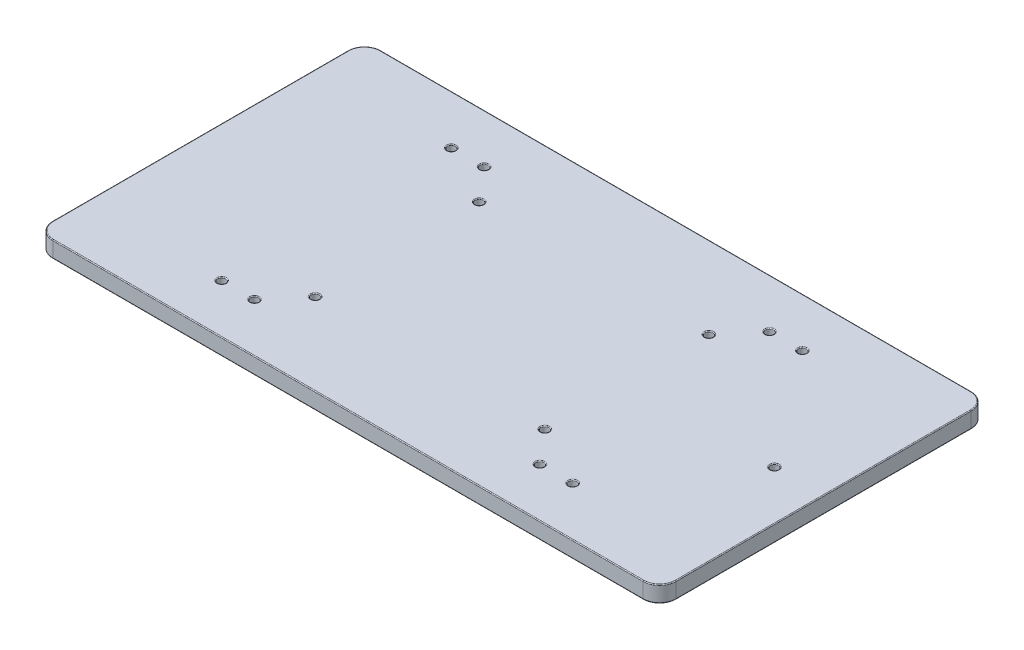
SolidWorks part; units mm, degrees
ref_plane "Front Plane" through (0, 0, 0) normal (0, 0, 1) x (1, 0, 0)
ref_plane "Top Plane" through (0, 0, 0) normal (0, 1, 0) x (1, 0, 0)
ref_plane "Right Plane" through (0, 0, 0) normal (1, 0, 0) x (0, 0, -1)
sketch "Sketch1" plane through (0, 0, 0) normal (0, 1, 0) x (1, 0, 0)
  line L0 (80, 50) -> (80, -50) construction
  line L1 (-95, 50) -> (95, 50)
  line L2 (-95, 50) -> (-95, -50)
  line L3 (-95, -50) -> (95, -50)
  line L4 (95, 50) -> (95, -50)
  line L5 (-95, 50) -> (95, -50) construction
  line L6 (-95, -50) -> (95, 50) construction
  line L7 (-35, 25) -> (35, 25)
  line L8 (-35, 25) -> (-35, -25)
  line L9 (-35, -25) -> (35, -25)
  line L10 (35, 25) -> (35, -25)
  line L11 (-35, 25) -> (35, -25) construction
  line L12 (-35, -25) -> (35, 25) construction
  line L13 (0, 0) -> (23.7742, 0) construction
  line L14 (0, 0) -> (0, 18.2551) construction
  circle A0 centre (-35, 25) radius 1.25
  circle A1 centre (35, 25) radius 1.25
  circle A2 centre (35, -25) radius 1.25
  circle A3 centre (-35, -25) radius 1.25
  circle A4 centre (80, 0) radius 1.25
  circle A5 centre (-53.5, -35) radius 1.25
  circle A6 centre (-43.5, -35) radius 1.25
  circle A7 centre (-43.5, 35) radius 1.25
  circle A8 centre (-53.5, 35) radius 1.25
  circle A9 centre (43.5, -35) radius 1.25
  circle A10 centre (53.5, -35) radius 1.25
  circle A11 centre (53.5, 35) radius 1.25
  circle A12 centre (43.5, 35) radius 1.25
  point P0 (0, 0)
  point P6 (0, 0)
  dimension "D5" = 2.5
  dimension "D7" = 2.5
  dimension "D8" = 2.5
  dimension "D9" = 10
  dimension "D1" = 100
  dimension "D2" = 190
  dimension "D3" = 70
  dimension "D4" = 50
  dimension "D6" = 15
  dimension "D10" = 43.5
  dimension "D11" = 15
  dimension "D12" = 15
extrude "Boss-Extrude1" add sketch "Sketch1" along normal blind 5 contours L4 L1 L2 L3 A12 A11 A9 A7 A6 A5 A4 A3 L8 A0 L7 A1 L10 A2 L9 A8 A10 | A3 L9 A2 L10 A1 L7 A0 L8
fillet "Fillet1" radius 5 4 edges at (-95, 2.5, 50) (-95, 2.5, -50) (95, 2.5, -50) (95, 2.5, 50)
fillet "Fillet2" radius 0.25 42 edges at (-35, 5, 26.25) (-35, 0, 26.25) (35, 5, -23.75) (35, 0, -23.75) (35, 5, 26.25) (35, 0, 26.25) (43.5, 5, -33.75) (43.5, 0, -33.75) (53.5, 5, -33.75) (53.5, 0, -33.75) (43.5, 5, 36.25) (43.5, 0, 36.25) (-43.5, 5, -33.75) (-43.5, 0, -33.75) (-43.5, 5, 36.25) (-43.5, 0, 36.25) (-53.5, 5, 36.25) (-53.5, 0, 36.25) (80, 5, 1.25) (80, 0, 1.25) (-35, 5, -23.75) (-35, 0, -23.75) (95, 0, 0) (95, 5, 0) (0, 0, -50) (0, 5, -50) (-95, 0, 0) (-95, 5, 0) (0, 5, 50) (0, 0, 50) (-53.5, 5, -33.75) (-53.5, 0, -33.75) (53.5, 5, 36.25) (53.5, 0, 36.25) (93.5355, 5, 48.5355) (93.5355, 0, 48.5355) (93.5355, 5, -48.5355) (93.5355, 0, -48.5355) (-93.5355, 5, -48.5355) (-93.5355, 0, -48.5355) (-93.5355, 5, 48.5355) (-93.5355, 0, 48.5355)
